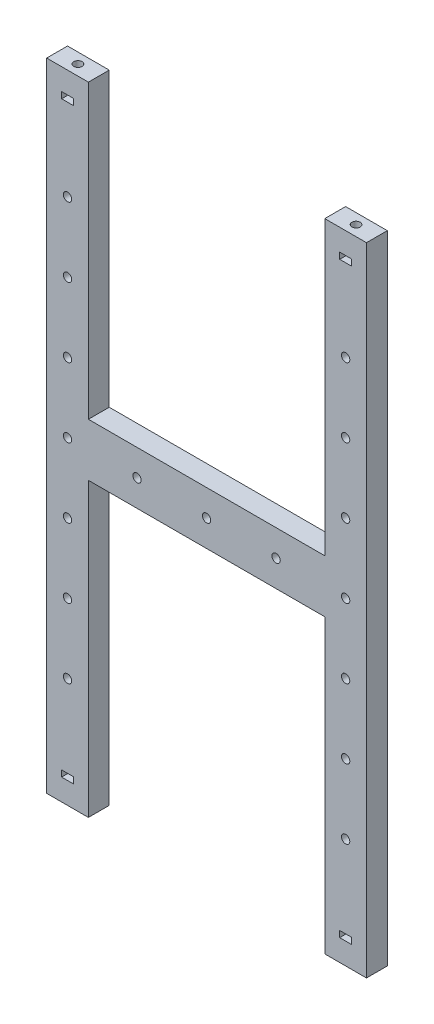
SolidWorks part; units mm, degrees
ref_plane "前视基准面" through (0, 0, 0) normal (0, 0, 1) x (1, 0, 0)
ref_plane "上视基准面" through (0, 0, 0) normal (0, 1, 0) x (1, 0, 0)
ref_plane "右视基准面" through (0, 0, 0) normal (1, 0, 0) x (0, 0, -1)
sketch "草图1" plane through (0, 0, 0) normal (0, 0, 1) x (1, 0, 0)
  line L0 (-115, 229) -> (-115, -229)
  line L9 (85, 19) -> (-85, 19)
  line L10 (-85, 19) -> (-85, 229)
  line L11 (-85, 229) -> (-115, 229)
  line L12 (85, 19) -> (85, 229)
  line L13 (-136.0137, 0) -> (236.1203, 0) construction
  line L14 (0, -361.3898) -> (0, 18.9648) construction
  line L15 (85, 229) -> (115, 229)
  line L16 (115, 229) -> (115, -229)
  line L17 (85, -229) -> (115, -229)
  line L18 (85, -19) -> (85, -229)
  line L19 (85, -19) -> (-85, -19)
  line L20 (-85, -19) -> (-85, -229)
  line L21 (-85, -229) -> (-115, -229)
  circle A0 centre (0, 0) radius 3
  circle A1 centre (50, 0) radius 3
  circle A2 centre (100, 0) radius 3
  circle A3 centre (-50, 0) radius 3
  circle A4 centre (-100, 0) radius 3
  circle A9 centre (100, 50) radius 3
  circle A10 centre (100, 100) radius 3
  circle A11 centre (100, 150) radius 3
  circle A13 centre (-100, -50) radius 3
  circle A14 centre (-100, -100) radius 3
  circle A15 centre (-100, -150) radius 3
  circle A17 centre (100, -50) radius 3
  circle A18 centre (100, -100) radius 3
  circle A19 centre (100, -150) radius 3
  circle A22 centre (100, 200) radius 3 [skipped]
  circle A23 centre (-100, -200) radius 3 [skipped]
  circle A24 centre (100, -200) radius 3 [skipped]
  circle A25 centre (-100, 50) radius 3
  circle A26 centre (-100, 100) radius 3
  circle A27 centre (-100, 150) radius 3
  point P7 (0, 19)
  point P19 (115, 0)
  point P24 (-115, 0)
  dimension "D5" = 3
  dimension "D7" = 4
  dimension "D12" = 6
  dimension "D1" = 30
  dimension "D2" = 229
  dimension "D3" = 210
  dimension "D4" = 85
  dimension "D6" = 3
  dimension "D9" = 5
  dimension "D10" = 5
  dimension "D11" = 5
extrude "凸台-拉伸1" add sketch "草图1" along normal blind 15
sketch "草图2" plane through (0, 229, 0) normal (0, 1, 0) x (1, 0, 0)
  line L0 (-85, 0) -> (-115, 0) construction
  line L2 (-115, -15) -> (-115, 0) construction
  circle A0 centre (-100, -7.5) radius 3
  dimension "D1" = 6
  dimension "D2" = 7.5
  dimension "D3" = 15
extrude "切除-拉伸1" cut sketch "草图2" against normal blind 30
mirror "镜向1" about plane through (0, 0, 0) normal (0, 1, 0) of "切除-拉伸1"
mirror "镜向2" about plane through (0, 0, 0) normal (1, 0, 0) of "镜向1", "切除-拉伸1"
ref_plane "基准面1" through (0, 209, 0) normal (0, 1, 0) x (1, 0, 0)
sketch "草图3" plane through (0, 209, 0) normal (0, 1, 0) x (1, 0, 0)
  line L0 (-104.25, -9.5859) -> (-104.25, -15)
  line L1 (-100, -2.5925) -> (-104.25, -5.0463)
  line L2 (-104.25, -5.0463) -> (-104.25, -9.5859)
  line L5 (-95.75, -9.7832) -> (-95.75, -5.0463)
  line L6 (-95.75, -5.0463) -> (-100, -2.5925)
  line L7 (-85, -15) -> (-115, -15) construction
  line L8 (-104.25, -15) -> (-95.75, -15)
  line L9 (-95.75, -15) -> (-95.75, -9.7832)
  line L11 (-97.875, -11.1806) -> (-95.825, -9.997) [skipped]
  line L12 (-103.9314, -10.1377) -> (-101.8814, -11.3212) [skipped]
  arc A0 (-95.75, -7.5) -> (-104.25, -7.5) centre (-100, -7.5) ccw construction
  dimension "D1" = 8.5
extrude "切除-拉伸2" cut sketch "草图3" along normal blind 4.5
mirror "镜向3" about plane through (0, 0, 0) normal (0, 1, 0) of "切除-拉伸2"
mirror "镜向4" about plane through (0, 0, 0) normal (1, 0, 0) of "镜向3", "切除-拉伸2"
